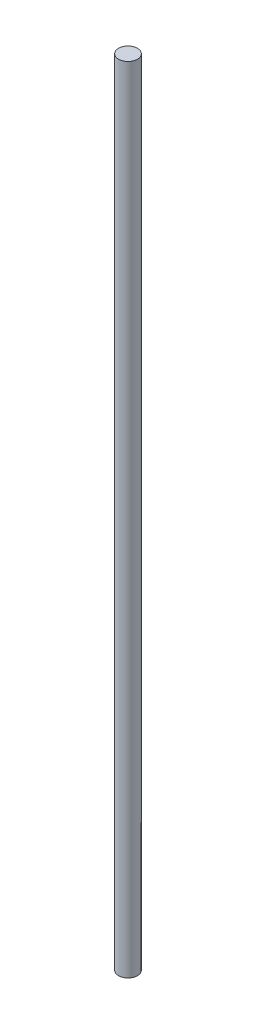
SolidWorks part; units mm, degrees
ref_plane "Front Plane" through (0, 0, 0) normal (0, 0, 1) x (1, 0, 0)
ref_plane "Top Plane" through (0, 0, 0) normal (0, 1, 0) x (1, 0, 0)
ref_plane "Right Plane" through (0, 0, 0) normal (1, 0, 0) x (0, 0, -1)
sketch "Sketch2" plane through (0, 0, 0) normal (0, 1, 0) x (1, 0, 0)
  circle A0 centre (0, 0) radius 25.4
extrude "Boss-Extrude1" add sketch "Sketch2" along normal blind 2133.6
